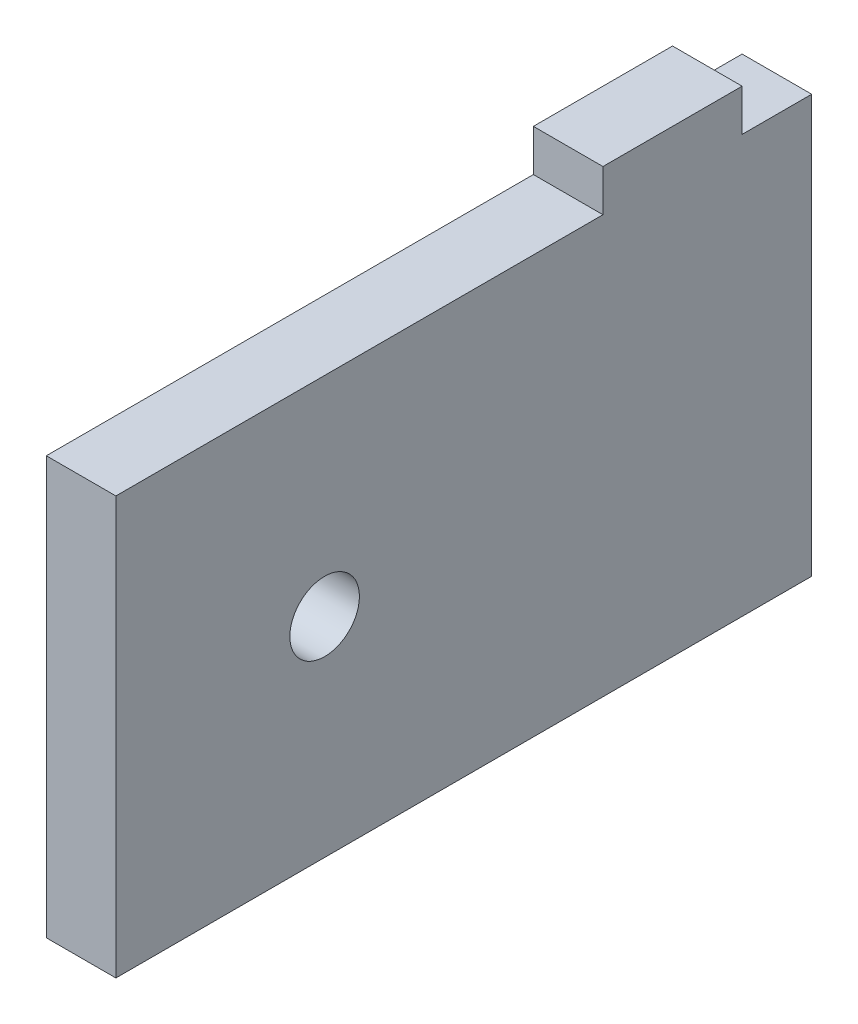
SolidWorks part; units mm, degrees
ref_plane "Front Plane" through (0, 0, 0) normal (0, 0, 1) x (1, 0, 0)
ref_plane "Top Plane" through (0, 0, 0) normal (0, 1, 0) x (1, 0, 0)
ref_plane "Right Plane" through (0, 0, 0) normal (1, 0, 0) x (0, 0, -1)
sketch "Sketch1" plane through (0, 0, 0) normal (1, 0, 0) x (0, 0, -1)
  line L1 (-25, -15) -> (25, -15)
  line L2 (-25, -15) -> (-25, 15)
  line L3 (-25, 15) -> (25, 15)
  line L4 (25, -15) -> (25, 15)
  line L5 (-25, -15) -> (25, 15) construction
  line L6 (-25, 15) -> (25, -15) construction
  point P0 (0, 0)
  dimension "D1" = 50
  dimension "D2" = 30
extrude "Extrude1" add sketch "Sketch1" along normal blind 5
sketch "Sketch2" plane through (5, 0, 0) normal (1, 0, 0) x (0, 0, -1)
  line L0 (25, 15) -> (-25, 15) construction
  line L1 (20, 15) -> (10, 15)
  line L2 (20, 15) -> (20, 18)
  line L3 (20, 18) -> (10, 18)
  line L4 (10, 15) -> (10, 18)
  line L5 (25, -15) -> (25, 15) construction
  dimension "D1" = 10
  dimension "D2" = 5
  dimension "D3" = 3
extrude "Extrude2" add sketch "Sketch2" against normal up to surface (5 mm away) up to face at (0, 0, 0)
sketch "Sketch3" plane through (5, 0, 0) normal (1, 0, 0) x (0, 0, -1)
  line L0 (0, 0) -> (-10, 0) construction
  circle A0 centre (-10, 0) radius 2.5
  dimension "D1" = 5
  dimension "D2" = 10
extrude "Cut-Extrude1" cut sketch "Sketch3" against normal through all
